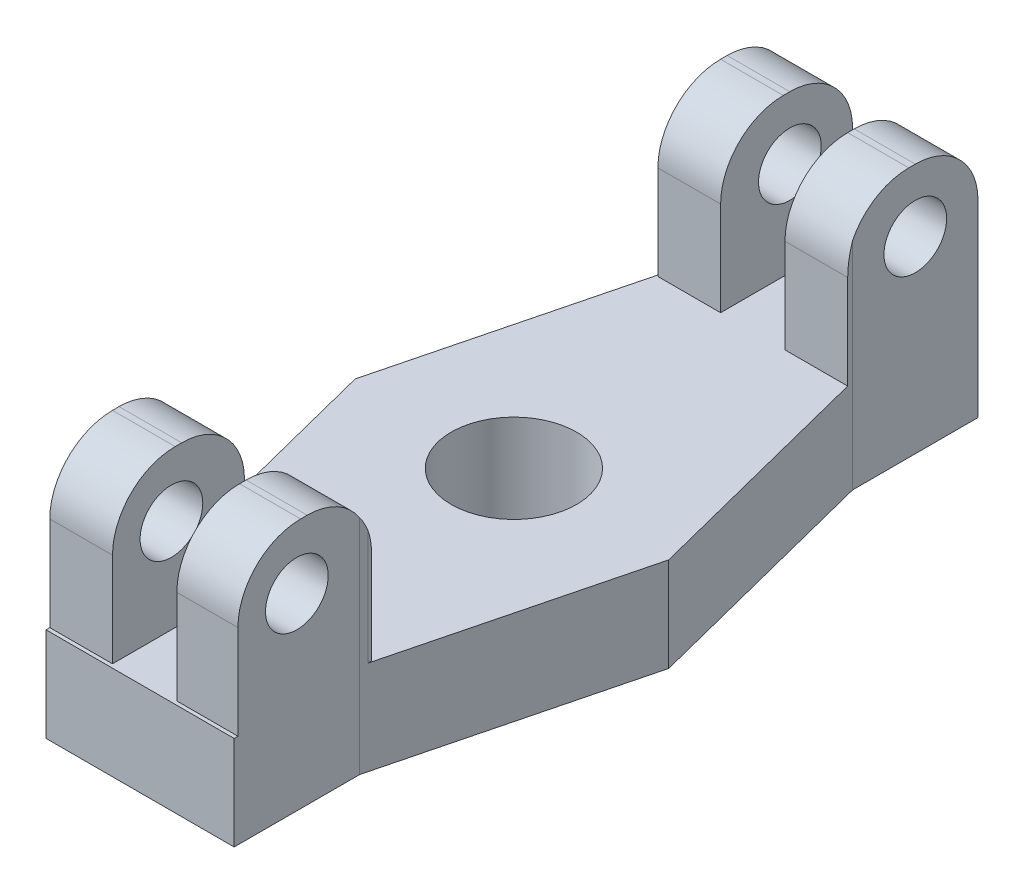
SolidWorks part; units mm, degrees
ref_plane "Front Plane" through (0, 0, 0) normal (0, 0, 1) x (1, 0, 0)
ref_plane "Top Plane" through (0, 0, 0) normal (0, 1, 0) x (1, 0, 0)
ref_plane "Right Plane" through (0, 0, 0) normal (1, 0, 0) x (0, 0, -1)
sketch "Sketch1" plane through (0, 0, 0) normal (0, 1, 0) x (1, 0, 0)
  line L0 (0, -0.9963) -> (0, 49.0037) construction
  line L1 (15, 39.0037) -> (24.9904, -0.3019)
  line L2 (-15, 39.0037) -> (-24.9904, -0.3019)
  line L3 (-15, 59.0037) -> (15, 59.0037)
  line L4 (-15, 59.0037) -> (-15, 39.0037)
  line L5 (-15, 39.0037) -> (15, 39.0037)
  line L6 (15, 59.0037) -> (15, 39.0037)
  line L7 (-15, 59.0037) -> (15, 39.0037) construction
  line L8 (-15, 39.0037) -> (15, 59.0037) construction
  line L9 (-24.9904, -0.3019) -> (24.9904, -0.3019) construction
  line L10 (-15, -39.6075) -> (15, -59.6075) construction
  line L11 (-15, -59.6075) -> (15, -39.6075) construction
  line L12 (15, -59.6075) -> (15, -39.6075)
  line L13 (-15, -39.6075) -> (15, -39.6075)
  line L14 (-15, -59.6075) -> (-15, -39.6075)
  line L15 (-15, -59.6075) -> (15, -59.6075)
  line L16 (15, -39.6075) -> (24.9904, -0.3019)
  line L17 (-15, -39.6075) -> (-24.9904, -0.3019)
  circle A0 centre (0, 0) radius 10
  dimension "D1" = 20
  dimension "D2" = 50
  dimension "D3" = 30
  dimension "D4" = 20
  dimension "D5" = 25
extrude "Boss-Extrude1" add sketch "Sketch1" along normal blind 15 contours L17 L13 L16 L1 L5 L2 A0 | L14 L15 L12 L13 | L6 L3 L4 L5
sketch "Sketch2" plane through (0, 15, 0) normal (0, 1, 0) x (1, 0, 0)
  line L0 (15, 39.0037) -> (24.9904, -0.3019) construction
  line L1 (-15, 59.0037) -> (15.2647, 59.0037)
  line L2 (-15, 59.0037) -> (-15, 37.9622)
  line L3 (-15, 37.9622) -> (15.2647, 37.9622)
  line L4 (15.2647, 59.0037) -> (15.2647, 37.9622)
  line L5 (-15, 59.0037) -> (15.2647, 37.9622) construction
  line L6 (-15, 37.9622) -> (15.2647, 59.0037) construction
  line L7 (-5, 59.0037) -> (-5, 37.9622)
  line L8 (0.1324, 37.9622) -> (0.1324, 59.0037) construction
  line L9 (5.2647, 59.0037) -> (5.2647, 37.9622)
  line L10 (0, 0) -> (27.2563, 0) construction
  line L11 (0.1324, -37.9622) -> (0.1324, -59.0037) construction
  line L12 (-15, -37.9622) -> (15.2647, -59.0037) construction
  line L13 (-15, -59.0037) -> (15.2647, -37.9622) construction
  line L14 (5.2647, -59.0037) -> (5.2647, -37.9622)
  line L15 (-5, -59.0037) -> (-5, -37.9622)
  line L16 (15.2647, -59.0037) -> (15.2647, -37.9622)
  line L17 (-15, -37.9622) -> (15.2647, -37.9622)
  line L18 (-15, -59.0037) -> (-15, -37.9622)
  line L19 (-15, -59.0037) -> (15.2647, -59.0037)
  point P4 (0.1324, 48.483)
  point P27 (0.1324, -48.483)
  line M14 (-15, -39.6075) -> (-15, -59.6075)
  line M16 (15, -59.6075) -> (15, -39.6075)
  line M17 (15, -39.6075) -> (24.9904, -0.3019)
  line M18 (24.9904, -0.3019) -> (15, 39.0037)
  line M19 (15, 39.0037) -> (15, 59.0037)
  line M20 (15, 59.0037) -> (-15, 59.0037)
  line M21 (-15, 59.0037) -> (-15, 39.0037)
  dimension "D1" = 10
extrude "Boss-Extrude2" add sketch "Sketch2" along normal blind 25 contours L9 L3 M20 M18 M19 | L7 L1 L2 L3 M21 | L19 L15 L17 L18 M14 | L14 L19 L16 L17 M16 M17
sketch "Sketch3" plane through (15, 0, 0) normal (1, 0, 0) x (0, 0, -1)
  line L0 (-0.3019, 0) -> (-0.3019, 45.2499) construction
  line L1 (-39.6075, 40) -> (-39.6075, 0) construction
  line L2 (-59.0037, 40) -> (-39.6075, 40) construction
  circle A0 centre (-49.6075, 30) radius 5
  circle A1 centre (49.0037, 30) radius 5
  dimension "D1" = 10
  dimension "D2" = 10
  dimension "D3" = 10
extrude "Cut-Extrude1" cut sketch "Sketch3" against normal blind 58
fillet "Fillet1" radius 10 8 edges at (10.1324, 40, -59.0037) (10.2647, 40, -37.9622) (-10, 40, -59.0037) (-10, 40, -37.9622) (10.2647, 40, 37.9622) (-10, 40, 37.9622) (10.1324, 40, 59.0037) (-10, 40, 59.0037)
